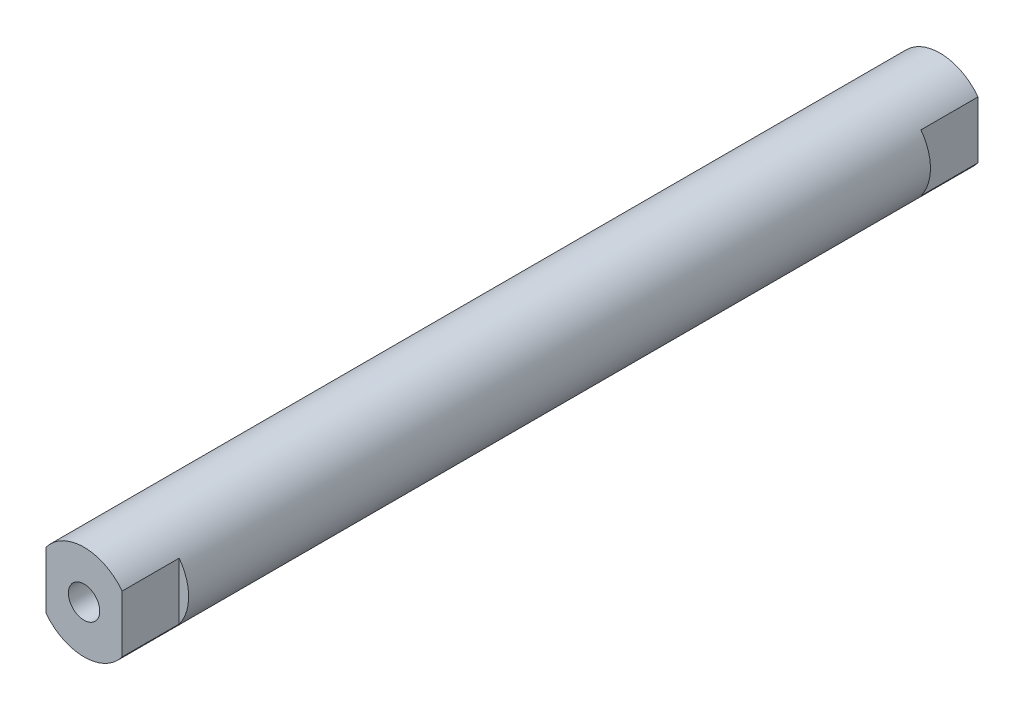
SolidWorks part; units mm, degrees
ref_plane "前视基准面" through (0, 0, 0) normal (0, 0, 1) x (1, 0, 0)
ref_plane "上视基准面" through (0, 0, 0) normal (0, 1, 0) x (1, 0, 0)
ref_plane "右视基准面" through (0, 0, 0) normal (1, 0, 0) x (0, 0, -1)
sketch "草图1" plane through (0, 0, 0) normal (0, 0, 1) x (1, 0, 0)
  circle A0 centre (0, 0) radius 5
  dimension "D1" = 10
extrude "凸台-拉伸1" add sketch "草图1" along normal mid plane 90
sketch "草图2" plane through (0, 0, 45) normal (0, 0, 1) x (1, 0, 0)
  line L0 (0, -1000) -> (0, 49000) construction
  line L2 (-4, -3) -> (-4, 3)
  line L4 (4, -3) -> (4, 3)
  line L5 (-2.2801, -5.5499) -> (0, 0) construction
  line L6 (0, 0) -> (2.2801, -5.5499) construction
  circle A0 centre (0, 0) radius 5 construction
  arc A1 (-4, 3) -> (-4, -3) centre (0, 0) ccw
  arc A2 (4, -3) -> (4, 3) centre (0, 0) ccw
  dimension "D1" = 8
extrude "切除-拉伸1" cut sketch "草图2" against normal blind 6
hole_wizard "M4 螺纹孔1" positions "草图4" profile "草图3" tap size "M4" standard "ISO"
sketch "草图4" plane through (0, 0, 45) normal (0, 0, 1) x (1, 0, 0)
  arc A0 (-4, -3) -> (4, -3) centre (0, 0) ccw construction
  point P0 (0, 0)
sketch "草图3" plane through (0, 0, 45) normal (1, 0, 0) x (0, -1, 0)
  line L0 (0, 0) -> (0, 11.0914)
  line L1 (0, 11.0914) -> (1.65, 10.1)
  line L2 (1.65, 10.1) -> (1.65, 0)
  line L5 (1.65, 0) -> (0, 0)
  line L10 (0, 11.0914) -> (-1.65, 10.1) construction
  line L11 (0, -6.35) -> (0, 107.95) construction
  dimension "螺纹孔钻头直径" = 3.3
  dimension "螺纹孔钻头深度" = 10.1
  dimension "导头角度" = 118
cosmetic thread "孔螺蚊线1" parameters "D1"=8, "D2"=4
mirror "镜向1" about plane through (0, 0, 0) normal (0, 0, 1) of "切除-拉伸1", "M4 螺纹孔1"
